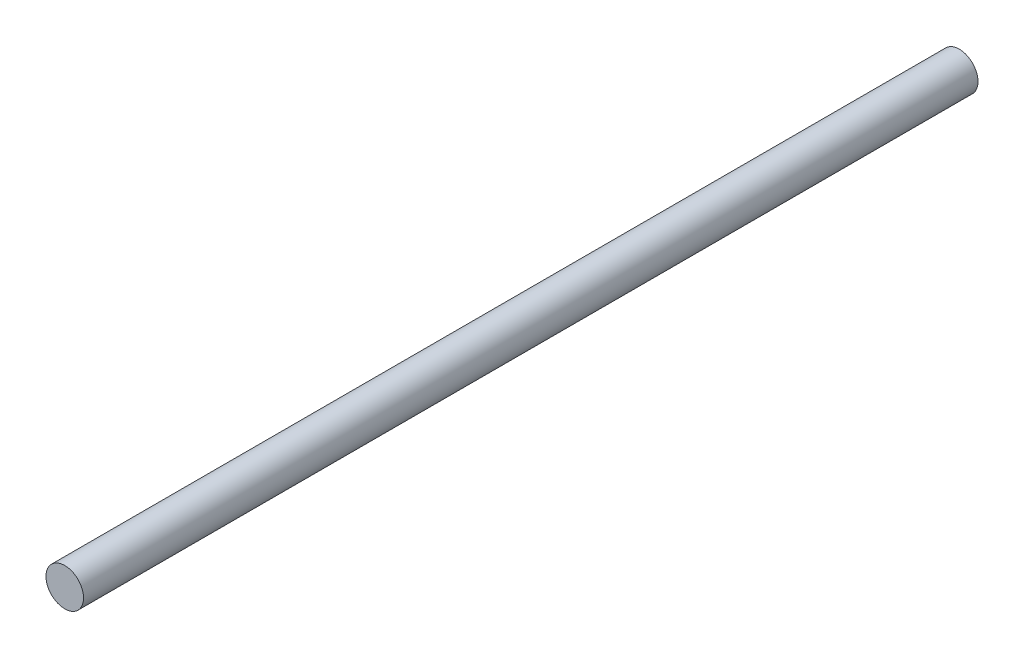
SolidWorks part; units mm, degrees
ref_plane "Front Plane" through (0, 0, 0) normal (0, 0, 1) x (1, 0, 0)
ref_plane "Top Plane" through (0, 0, 0) normal (0, 1, 0) x (1, 0, 0)
ref_plane "Right Plane" through (0, 0, 0) normal (1, 0, 0) x (0, 0, -1)
sketch "Sketch1" plane through (0, 0, 0) normal (0, 0, 1) x (1, 0, 0)
  circle A0 centre (0, 0) radius 1.25
  dimension "D1" = 2.5
extrude "Boss-Extrude1" add sketch "Sketch1" along normal blind 59.5
